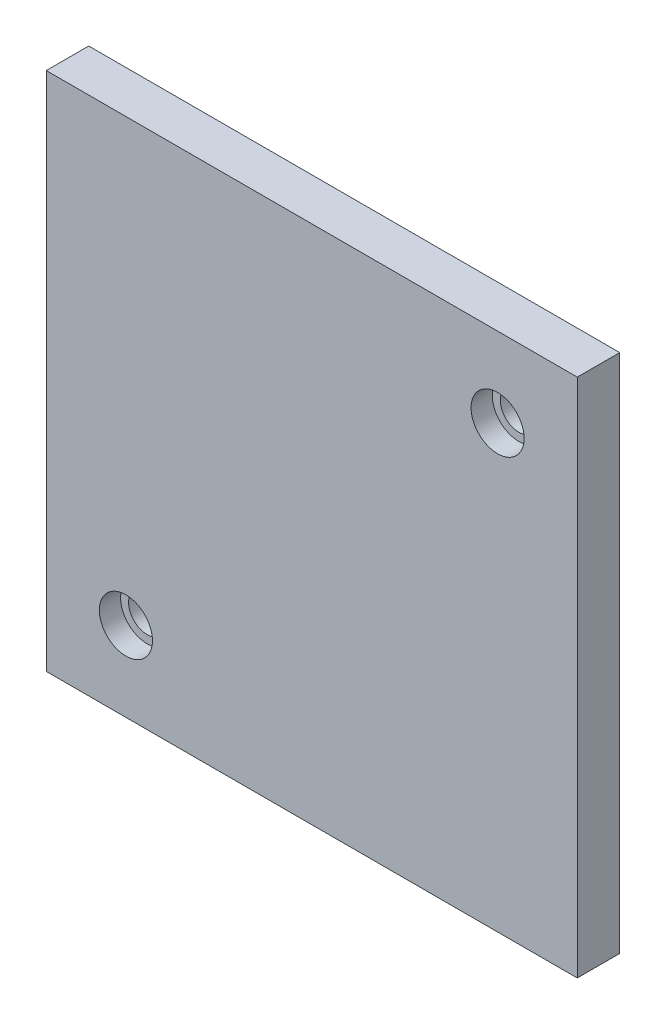
SolidWorks part; units mm, degrees
ref_plane "前视基准面" through (0, 0, 0) normal (0, 0, 1) x (1, 0, 0)
ref_plane "上视基准面" through (0, 0, 0) normal (0, 1, 0) x (1, 0, 0)
ref_plane "右视基准面" through (0, 0, 0) normal (1, 0, 0) x (0, 0, -1)
other "Configuration Table"
sketch "草图1" plane through (0, 0, 0) normal (0, 0, 1) x (1, 0, 0)
  line L1 (25, 24.5) -> (-25, 24.5)
  line L2 (25, 24.5) -> (25, -24.5)
  line L3 (25, -24.5) -> (-25, -24.5)
  line L4 (-25, 24.5) -> (-25, -24.5)
  line L5 (25, 24.5) -> (-25, -24.5) construction
  line L6 (25, -24.5) -> (-25, 24.5) construction
  point P0 (0, 0)
  dimension "D1" = 50
  dimension "D2" = 49
extrude "凸台-拉伸1" add sketch "草图1" along normal blind 4
sketch "草图2" plane through (0, 0, 4) normal (0, 0, 1) x (1, 0, 0)
  line L0 (-25, -24.5) -> (25, -24.5) construction
  line L1 (-25, 24.5) -> (-25, -24.5) construction
  line L2 (25, -24.5) -> (25, 24.5) construction
  line L3 (25, 24.5) -> (-25, 24.5) construction
  circle A0 centre (17.5, 17) radius 2.5
  circle A1 centre (-17.5, -17) radius 2.5
  point P8 (-27.6557, -16.1128)
  dimension "D1" = 7.5
  dimension "D3" = 5
  dimension "D4" = 7.5
  dimension "D6" = 5
  dimension "D2" = 7.5
  dimension "D5" = 7.5
extrude "切除-拉伸1" cut sketch "草图2" against normal blind 2
sketch "草图3" plane through (0, 0, 2) normal (0, 0, 1) x (1, 0, 0)
  circle A0 centre (-17.5, -17) radius 1.75
  circle A1 centre (17.5, 17) radius 1.75
  dimension "D1" = 3.5
  dimension "D2" = 3.5
extrude "切除-拉伸2" cut sketch "草图3" against normal blind 4
